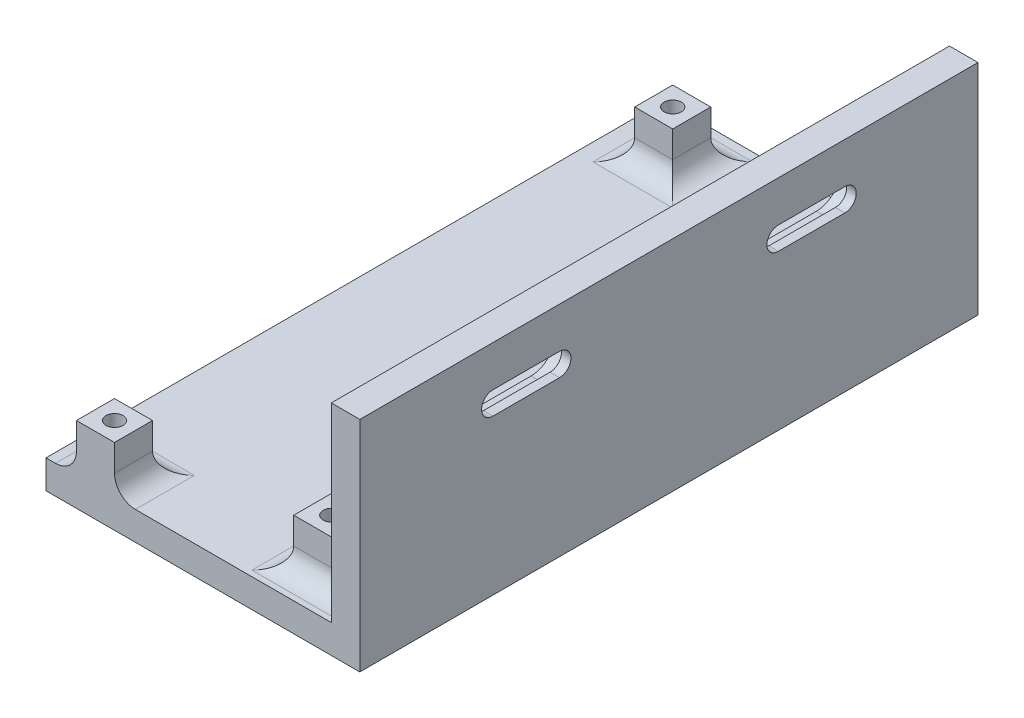
SolidWorks part; units mm, degrees
ref_plane "Front Plane" through (0, 0, 0) normal (0, 0, 1) x (1, 0, 0)
ref_plane "Top Plane" through (0, 0, 0) normal (0, 1, 0) x (1, 0, 0)
ref_plane "Right Plane" through (0, 0, 0) normal (1, 0, 0) x (0, 0, -1)
sketch "Sketch1" plane through (0, 0, 0) normal (0, 0, 1) x (1, 0, 0)
  line L0 (0, 0) -> (33, 0)
  line L1 (33, 0) -> (33, 35)
  line L2 (33, 35) -> (30, 35)
  line L3 (30, 35) -> (30, 3)
  line L4 (30, 3) -> (0, 3)
  line L5 (0, 3) -> (0, 0)
  dimension "D1" = 35
  dimension "D2" = 3
  dimension "D3" = 32
  dimension "D4" = 30
  dimension "D5" = 3
extrude "Boss-Extrude1" add sketch "Sketch1" along normal blind 65
sketch "Sketch2" plane through (0, 3, 0) normal (0, 1, 0) x (1, 0, 0)
  line L0 (0, -32.5) -> (30, -32.5)
  line L1 (0, -65) -> (0, 0) construction
  line L2 (30, -65) -> (30, 0) construction
  line L3 (15, -60.2) -> (15, -32.5)
  line L4 (15, -60.2) -> (25.25, -60.2)
  line L5 (27.25, -2.8) -> (23.25, -6.8) construction
  line L6 (27.25, -62.2) -> (23.25, -62.2)
  line L7 (27.25, -62.2) -> (27.25, -58.2)
  line L8 (27.25, -58.2) -> (23.25, -58.2)
  line L9 (23.25, -62.2) -> (23.25, -58.2)
  line L10 (27.25, -62.2) -> (23.25, -58.2) construction
  line L11 (27.25, -58.2) -> (23.25, -62.2) construction
  line L12 (27.25, -6.8) -> (23.25, -2.8) construction
  line L13 (27.25, -6.8) -> (23.25, -6.8)
  line L14 (23.25, -2.8) -> (23.25, -6.8)
  line L15 (27.25, -2.8) -> (23.25, -2.8)
  line L16 (27.25, -2.8) -> (27.25, -6.8)
  line L17 (15, -32.5) -> (15, -5.1)
  line L18 (15, -5.1) -> (6, -5.1)
  line L19 (15, -63) -> (5.2, -63)
  line L20 (8, -7.1) -> (4, -7.1)
  line L21 (8, -7.1) -> (8, -3.1)
  line L22 (8, -3.1) -> (4, -3.1)
  line L23 (4, -7.1) -> (4, -3.1)
  line L24 (8, -7.1) -> (4, -3.1) construction
  line L25 (8, -3.1) -> (4, -7.1) construction
  line L27 (7.2, -65) -> (3.2, -65)
  line L28 (7.2, -65) -> (7.2, -61)
  line L29 (7.2, -61) -> (3.2, -61)
  line L30 (3.2, -65) -> (3.2, -61)
  line L31 (7.2, -65) -> (3.2, -61) construction
  line L32 (7.2, -61) -> (3.2, -65) construction
  circle A0 centre (25.25, -60.2) radius 0.9
  circle A1 centre (25.25, -4.8) radius 0.9
  circle A2 centre (6, -5.1) radius 0.9
  circle A3 centre (5.2, -63) radius 0.9
  point P13 (25.25, -4.8)
  dimension "D5" = 1.8
  dimension "D10" = 1.8
  dimension "D15" = 1.8
  dimension "D2" = 10.25
  dimension "D3" = 4
  dimension "D4" = 4
  dimension "D6" = 27.4
  dimension "D7" = 9
  dimension "D8" = 4
  dimension "D9" = 4
  dimension "D11" = 9.8
  dimension "D12" = 30.5
  dimension "D13" = 4
  dimension "D14" = 4
  dimension "D16" = 27.7
extrude "Boss-Extrude2" add sketch "Sketch2" along normal blind 5
sketch "Sketch3" plane through (0, 3, 0) normal (0, 1, 0) x (1, 0, 0)
  line L0 (30, -32.5) -> (0, -32.5)
  line L1 (30, -65) -> (30, 0) construction
  line L2 (0, -65) -> (0, 0) construction
  line L3 (0, -32.5) -> (15, -32.5)
  line L4 (15, -32.5) -> (15, -17)
  line L5 (15, -17) -> (18.19, -17)
  line L6 (30, -22.8727) -> (30, -12.3727)
  line L8 (30, -22.8727) -> (13.5, -22.8727)
  line L9 (13.5, -22.8727) -> (13.5, -12.3727)
  line L10 (13.5, -12.3727) -> (30, -12.3727)
  dimension "D1" = 15.5
  dimension "D2" = 3.19
  dimension "D3" = 16.5
  dimension "D4" = 10.5
extrude "Cut-Extrude2" cut sketch "Sketch3" against normal up to next
sketch "Sketch4" plane through (33, 0, 0) normal (1, 0, 0) x (0, 0, -1)
  line L0 (-32.5, 35) -> (-32.5, 0)
  line L1 (-65, 35) -> (0, 35) construction
  line L2 (-65, 0) -> (0, 0) construction
  line L3 (-32.5, 17.5) -> (-47.5, 17.5)
  line L4 (-44.0019, 17.5) -> (-50.9981, 17.5) construction
  line L5 (-44.0019, 16.3) -> (-50.9981, 16.3)
  line L6 (-44.0019, 18.7) -> (-50.9981, 18.7)
  line L7 (-20.9981, 17.5) -> (-14.0019, 17.5) construction
  line L8 (-20.9981, 16.3) -> (-14.0019, 16.3)
  line L9 (-20.9981, 18.7) -> (-14.0019, 18.7)
  arc A0 (-44.0019, 16.3) -> (-44.0019, 18.7) centre (-44.0019, 17.5) ccw
  arc A1 (-50.9981, 18.7) -> (-50.9981, 16.3) centre (-50.9981, 17.5) ccw
  arc A2 (-20.9981, 16.3) -> (-20.9981, 18.7) centre (-20.9981, 17.5) cw
  arc A3 (-14.0019, 18.7) -> (-14.0019, 16.3) centre (-14.0019, 17.5) cw
  point P11 (-47.5, 17.5)
  point P17 (-17.5, 17.5)
  dimension "D2" = 1.2
  dimension "D1" = 15
extrude "Cut-Extrude3" cut sketch "Sketch4" against normal up to next
sketch "Sketch5" plane through (30, 0, 0) normal (-1, 0, 0) x (0, 0, 1)
  line L0 (20.9981, 17.5) -> (14.0019, 17.5) construction
  line L1 (20.9981, 14.95) -> (14.0019, 14.95)
  line L2 (20.9981, 20.05) -> (14.0019, 20.05)
  line L3 (44.0019, 17.5) -> (50.9981, 17.5) construction
  line L4 (44.0019, 20.05) -> (50.9981, 20.05)
  line L5 (44.0019, 14.95) -> (50.9981, 14.95)
  arc A0 (20.9981, 14.95) -> (20.9981, 20.05) centre (20.9981, 17.5) ccw
  arc A1 (14.0019, 20.05) -> (14.0019, 14.95) centre (14.0019, 17.5) ccw
  arc A2 (44.0019, 20.05) -> (44.0019, 14.95) centre (44.0019, 17.5) ccw
  arc A3 (50.9981, 14.95) -> (50.9981, 20.05) centre (50.9981, 17.5) ccw
  point P4 (17.5, 17.5)
  point P9 (47.5, 17.5)
  dimension "D1" = 2.55
  dimension "D2" = 2.55
extrude "Cut-Extrude4" cut sketch "Sketch5" against normal blind 2
fillet "Fillet1" radius 2.2 15 edges at (27.25, 3, 60.2) (25.25, 3, 62.2) (25.25, 3, 58.2) (23.25, 3, 60.2) (7.2, 3, 63) (5.2, 3, 61) (3.2, 3, 63) (27.25, 3, 4.8) (25.25, 3, 6.8) (25.25, 3, 2.8) (23.25, 3, 4.8) (8, 3, 5.1) (6, 3, 7.1) (6, 3, 3.1) (4, 3, 5.1)
sketch "Sketch7" plane through (30, 0, 0) normal (-1, 0, 0) x (0, 0, 1)
  line L0 (65, 35) -> (65, 3) construction
  line L1 (0, 35) -> (65, 35)
  line L2 (0, 35) -> (0, 23)
  line L3 (0, 23) -> (65, 23)
  line L4 (65, 35) -> (65, 23)
  dimension "D1" = 12
extrude "Cut-Extrude5" cut sketch "Sketch7" against normal up to next
